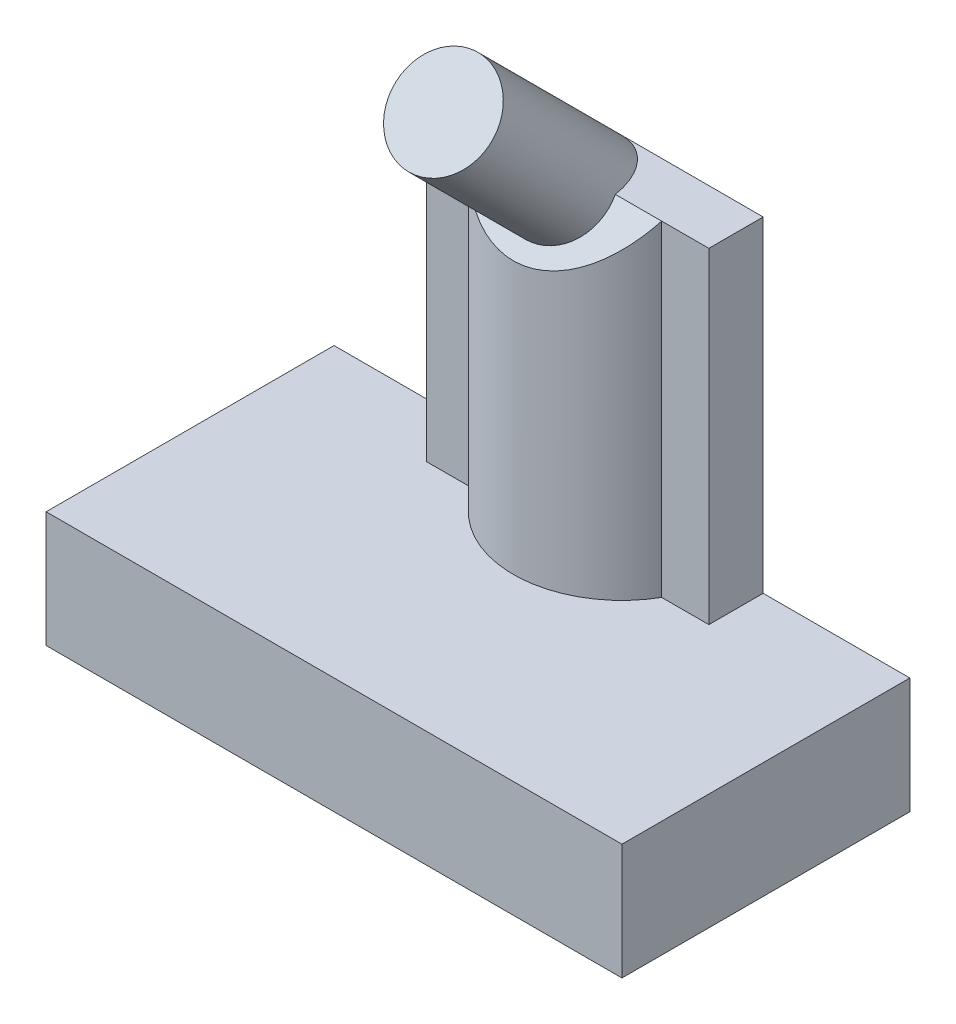
SolidWorks part; units mm, degrees
ref_plane "Front Plane" through (0, 0, 0) normal (0, 0, 1) x (1, 0, 0)
ref_plane "Top Plane" through (0, 0, 0) normal (0, 1, 0) x (1, 0, 0)
ref_plane "Right Plane" through (0, 0, 0) normal (1, 0, 0) x (0, 0, -1)
sketch "Sketch1" plane through (0, 0, 0) normal (0, 1, 0) x (1, 0, 0)
  line L1 (-7.95, -3.975) -> (7.95, -3.975)
  line L2 (-7.95, -3.975) -> (-7.95, 3.975)
  line L3 (-7.95, 3.975) -> (7.95, 3.975)
  line L4 (7.95, -3.975) -> (7.95, 3.975)
  line L5 (-7.95, -3.975) -> (7.95, 3.975) construction
  line L6 (-7.95, 3.975) -> (7.95, -3.975) construction
  point P0 (0, 0)
  dimension "D1" = 7.95
  dimension "D2" = 15.9
extrude "Boss-Extrude1" add sketch "Sketch1" along normal blind 3.2
shell "Shell1" thickness 1.2
sketch "Sketch3" plane through (0, 2, 0) normal (0, -1, 0) x (1, 0, 0)
  circle A0 centre (0, 0) radius 1.525
  circle A1 centre (0, 0) radius 0.5
  dimension "D1" = 3.05
  dimension "D2" = 1
extrude "Boss-Extrude3" add sketch "Sketch3" along normal up to surface (2 mm away) up to face at (0, 0, 0)
sketch "Sketch4" plane through (0, 3.2, 0) normal (0, 1, 0) x (1, 0, 0)
  line L0 (-3.9, 3.975) -> (-3.9, 2.475)
  line L1 (7.95, 3.975) -> (-7.95, 3.975) construction
  line L2 (-3.9, 2.475) -> (-2.5981, 2.475)
  line L3 (3.9, 2.475) -> (3.9, 3.975)
  line L4 (3.9, 3.975) -> (-3.9, 3.975)
  line L5 (2.5981, 2.475) -> (3.9, 2.475)
  arc A0 (-2.5981, 2.475) -> (2.5981, 2.475) centre (0, 3.975) ccw
  point P13 (0, 3.975)
  dimension "D1" = 3
  dimension "D2" = 7.8
  dimension "D3" = 1.5
extrude "Boss-Extrude4" add sketch "Sketch4" along normal blind 9
ref_plane "Plane1" through (0, 8.0875, 8.0875) normal (0, 0.7071, 0.7071) x (1, 0, 0)
ref_plane "Plane2" through (0, 4.8631, 4.8631) normal (0, 0.7071, 0.7071) x (1, 0, 0)
sketch "Sketch7" plane through (0, 4.8631, 4.8631) normal (0, 0.7071, 0.7071) x (1, 0, 0)
  line L1 (15, -15) -> (-15, -15)
  line L2 (15, -15) -> (15, 15)
  line L3 (15, 15) -> (-15, 15)
  line L4 (-15, -15) -> (-15, 15)
  line L5 (15, -15) -> (-15, 15) construction
  line L6 (15, 15) -> (-15, -15) construction
  point P0 (0, 0)
  dimension "D1" = 30
extrude "Cut-Extrude1" cut sketch "Sketch7" along normal through all
sketch "Sketch8" plane through (0, 8.0875, 8.0875) normal (0, 0.7071, 0.7071) x (1, 0, 0)
  line L0 (3.9, 11.4375) -> (-3.9, 11.4375) construction
  line L1 (0, 0) -> (0, 10.0875) construction
  circle A0 centre (0, 10.0875) radius 1.35
  dimension "D1" = 2.7
extrude "Boss-Extrude5" add sketch "Sketch8" against normal up to vertex (4.56 mm away)
